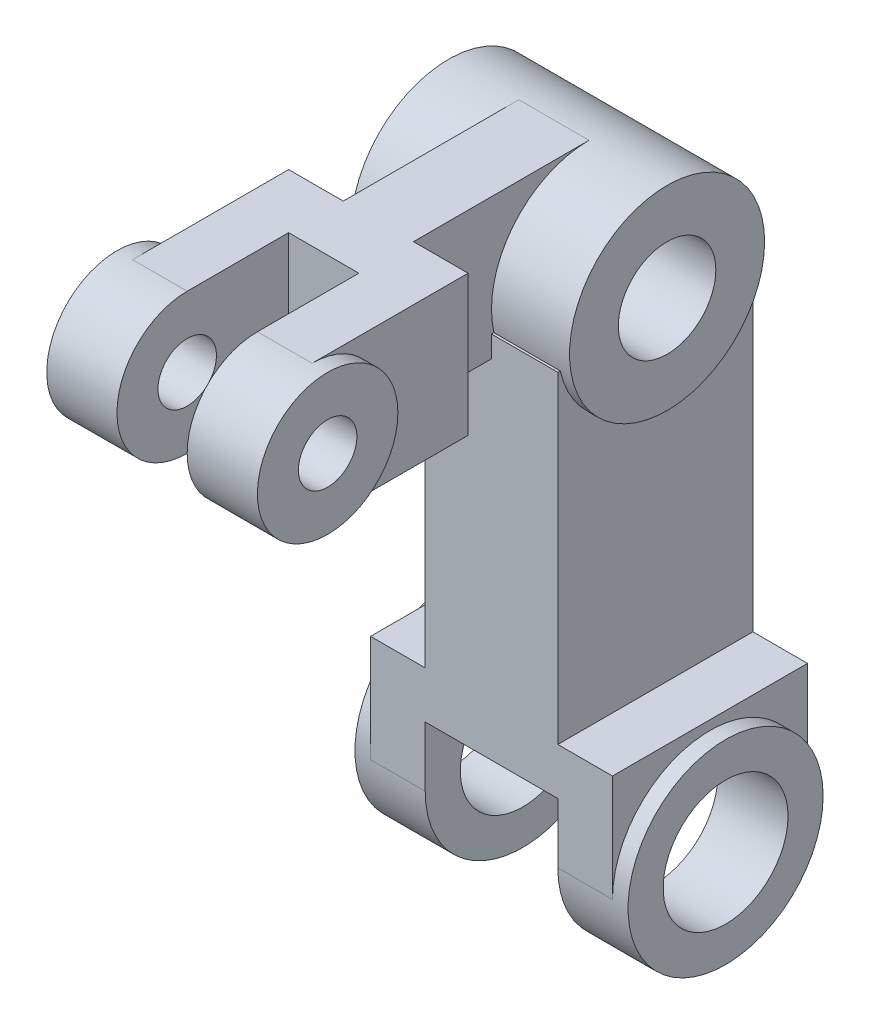
SolidWorks part; units mm, degrees
ref_plane "Front Plane" through (0, 0, 0) normal (0, 0, 1) x (1, 0, 0)
ref_plane "Top Plane" through (0, 0, 0) normal (0, 1, 0) x (1, 0, 0)
ref_plane "Right Plane" through (0, 0, 0) normal (1, 0, 0) x (0, 0, -1)
sketch "Sketch1" plane through (0, 0, 0) normal (0, 0, 1) x (1, 0, 0)
  line L0 (-31, 0) -> (-17, 0)
  line L1 (-17, 0) -> (-17, 15.39)
  line L2 (-17, 15.39) -> (17, 15.39)
  line L3 (17, 15.39) -> (17, 0)
  line L4 (17, 0) -> (31, 0)
  line L7 (-31, 27.39) -> (-31, 0)
  line L8 (0, 0) -> (0, 35.4364) construction
  line L9 (-17, 110) -> (17, 110)
  line L10 (-17, 110) -> (-17, 27.39)
  line L11 (-17, 27.39) -> (-31, 27.39)
  line L12 (17, 110) -> (17, 27.39)
  line L13 (17, 27.39) -> (31, 27.39)
  line L14 (31, 27.39) -> (31, 0)
  dimension "D1" = 34
  dimension "D2" = 110
  dimension "D3" = 12
  dimension "D4" = 14
  dimension "D5" = 27.39
extrude "Boss-Extrude1" add sketch "Sketch1" along normal mid plane 50
sketch "Sketch2" plane through (-17, 0, 0) normal (1, 0, 0) x (0, 0, -1)
  circle A0 centre (0, 0) radius 25
  dimension "D1" = 50
extrude "Boss-Extrude2" add sketch "Sketch2" against normal blind 18
mirror "Mirror1" about plane through (0, 0, 0) normal (1, 0, 0) of "Boss-Extrude2"
ref_plane "Plane1" through (0, 122.5, 0) normal (0, 1, 0) x (1, 0, 0)
sketch "Sketch3" plane through (0, 122.5, 0) normal (0, 1, 0) x (1, 0, 0)
  line L22 (-18, 0) -> (0, 0)
  line L23 (0, 0) -> (0, -45)
  line L24 (0, -45) -> (14, -45)
  line L25 (14, -45) -> (14, -85)
  line L26 (14, -85) -> (0, -85)
  line L27 (0, -85) -> (0, -59)
  line L28 (0, -59) -> (-18, -59)
  line L29 (-18, -59) -> (-18, -85)
  line L30 (-18, -85) -> (-32, -85)
  line L31 (-32, -85) -> (-32, -45)
  line L32 (-32, -45) -> (-18, -45)
  line L33 (-18, -45) -> (-18, 0)
  point P0 (0, 0)
  dimension "D1" = 18
  dimension "D2" = 14
  dimension "D3" = 14
  dimension "D4" = 85
  dimension "D5" = 40
  dimension "D6" = 18
extrude "Boss-Extrude3" add sketch "Sketch3" against normal mid plane 36
sketch "Sketch4" plane through (0, 0, 0) normal (1, 0, 0) x (0, 0, -1)
  circle A1 centre (0, 115.5) radius 25
  dimension "D1" = 50
extrude "Boss-Extrude4" add sketch "Sketch4" along normal blind 20 and the other way blind 36
sketch "Sketch5" plane through (0, 0, 0) normal (1, 0, 0) x (0, 0, -1)
  line L0 (-85, 104.5) -> (-85, 140.5) construction
  circle A0 centre (-85, 122.5) radius 18
extrude "Boss-Extrude5" add sketch "Sketch5" along normal blind 18
sketch "Sketch6" plane through (-18, 0, 0) normal (1, 0, 0) x (0, 0, -1)
  circle A0 centre (-85, 122.5) radius 18 construction
  circle A1 centre (-85, 122.5) radius 18
extrude "Boss-Extrude6" add sketch "Sketch6" against normal blind 18
hole_wizard "Hole1" positions "Sketch7" profile "Sketch8" legacy end condition through all
sketch "Sketch7" plane through (35, 0, 0) normal (1, 0, 0) x (0, 0, -1)
  point P0 (0, 0)
sketch "Sketch8" plane through (35, 0, 0) normal (0, 1, 0) x (0, 0, -1)
  line L0 (0, 0) -> (0, 71)
  line L1 (0, 71) -> (16, 71)
  line L2 (16, 71) -> (16, 0)
  line L3 (16, 0) -> (0, 0)
  line L4 (0, 110) -> (0, -10) construction
  dimension "Diameter" = 32
  dimension "Depth" = 71
hole_wizard "Hole2" positions "Sketch9" profile "Sketch10" legacy end condition through all
sketch "Sketch9" plane through (20, 0, 0) normal (1, 0, 0) x (0, 0, -1)
  point P0 (0, 115.5)
sketch "Sketch10" plane through (20, 115.5, 0) normal (0, 1, 0) x (0, 0, -1)
  line L0 (0, 0) -> (0, 56)
  line L1 (0, 56) -> (12.5, 56)
  line L2 (12.5, 56) -> (12.5, 0)
  line L3 (12.5, 0) -> (0, 0)
  line L4 (0, 110) -> (0, -10) construction
  dimension "Diameter" = 25
  dimension "Depth" = 56
hole_wizard "Hole3" positions "Sketch11" profile "Sketch12" legacy end condition through all
sketch "Sketch11" plane through (18, 0, 0) normal (1, 0, 0) x (0, 0, -1)
  point P0 (-85, 122.5)
sketch "Sketch12" plane through (18, 122.5, 85) normal (0, 1, 0) x (0, 0, -1)
  line L0 (0, 0) -> (0, 54)
  line L1 (0, 54) -> (7.5, 54)
  line L2 (7.5, 54) -> (7.5, 0)
  line L3 (7.5, 0) -> (0, 0)
  line L4 (0, 110) -> (0, -10) construction
  point P2 (0, 0)
  dimension "Diameter" = 15
  dimension "Depth" = 54
